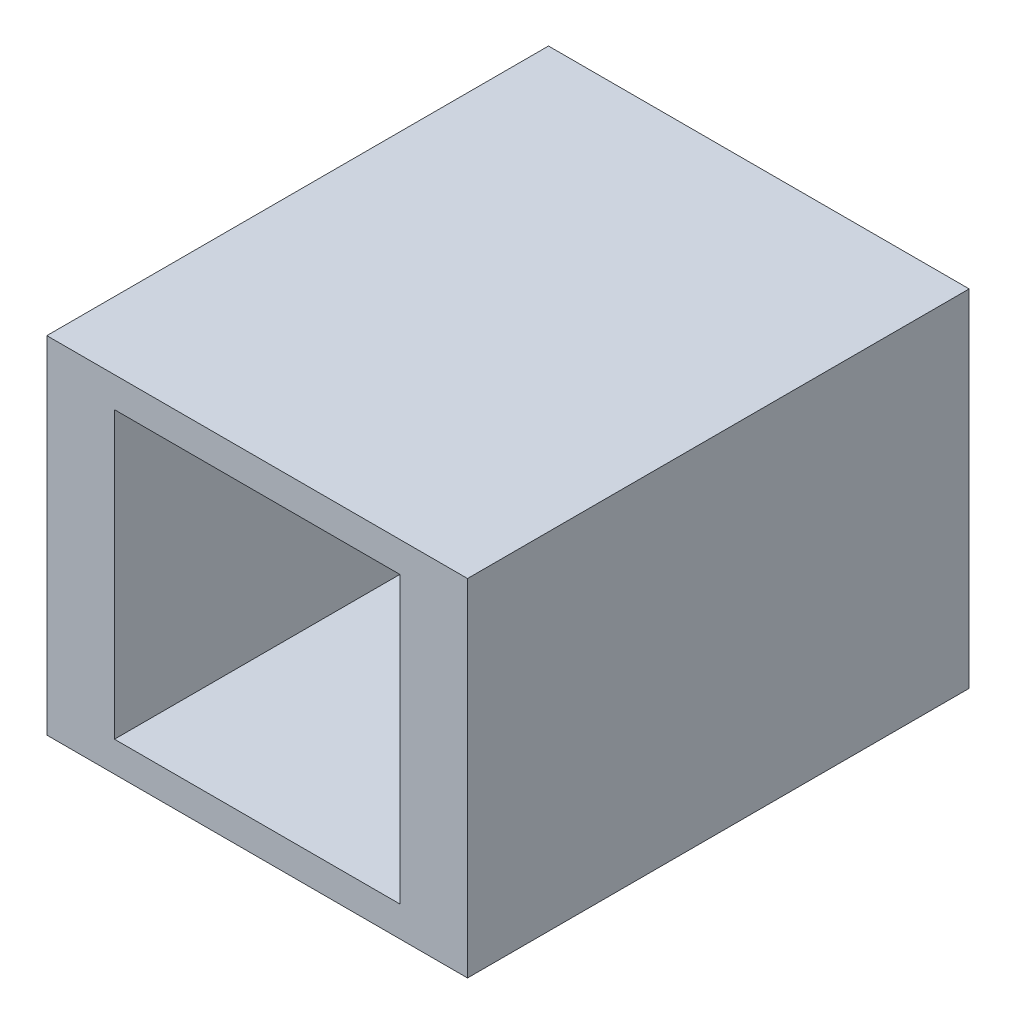
SolidWorks part; units mm, degrees
ref_plane "前基準面" through (0, 0, 0) normal (0, 0, 1) x (1, 0, 0)
ref_plane "上基準面" through (0, 0, 0) normal (0, 1, 0) x (1, 0, 0)
ref_plane "右基準面" through (0, 0, 0) normal (1, 0, 0) x (0, 0, -1)
sketch "草圖1" plane through (0, 0, 0) normal (0, 0, 1) x (1, 0, 0)
  line L1 (-8.25, 8.25) -> (8.25, 8.25)
  line L2 (-8.25, 8.25) -> (-8.25, -8.25)
  line L3 (-8.25, -8.25) -> (8.25, -8.25)
  line L4 (8.25, 8.25) -> (8.25, -8.25)
  line L5 (-8.25, 8.25) -> (8.25, -8.25) construction
  line L6 (-8.25, -8.25) -> (8.25, 8.25) construction
  line L7 (-12.16, 10) -> (12.16, 10)
  line L8 (-12.16, 10) -> (-12.16, -10)
  line L9 (-12.16, -10) -> (12.16, -10)
  line L10 (12.16, 10) -> (12.16, -10)
  line L11 (-12.16, 10) -> (12.16, -10) construction
  line L12 (-12.16, -10) -> (12.16, 10) construction
  point P0 (0, 0)
  point P6 (0, 0)
  dimension "D1" = 16.5
  dimension "D2" = 24.32
  dimension "D3" = 20
extrude "填料-伸長1" add sketch "草圖1" along normal blind 29
sketch "草圖2" plane through (0, 0, 0) normal (0, 0, 1) x (1, 0, 0)
  line L1 (-8.25, 8.25) -> (8.25, 8.25)
  line L2 (-8.25, 8.25) -> (-8.25, -8.25)
  line L3 (-8.25, -8.25) -> (8.25, -8.25)
  line L4 (8.25, 8.25) -> (8.25, -8.25)
  line L5 (-8.25, 8.25) -> (8.25, -8.25) construction
  line L6 (-8.25, -8.25) -> (8.25, 8.25) construction
  line L7 (-12.16, 10) -> (12.16, 10) construction
  line L8 (-12.16, 10) -> (-12.16, -10) construction
  line L9 (-12.16, -10) -> (12.16, -10)
  line L10 (12.16, 10) -> (12.16, -10) construction
  line L11 (-12.16, 10) -> (12.16, -10) construction
  line L12 (-12.16, -10) -> (12.16, 10) construction
  point P0 (0, 0)
  point P5 (0, 0)
  point P6 (0, 0)
  point P11 (0, 0)
  point P12 (0, 0)
  point P13 (0, 0)
  dimension "D1" = 16.5
  dimension "D2" = 24.32
  dimension "D3" = 20
extrude "填料-伸長2" add sketch "草圖2" along normal blind 1 contours L4 L1 L2 L3
